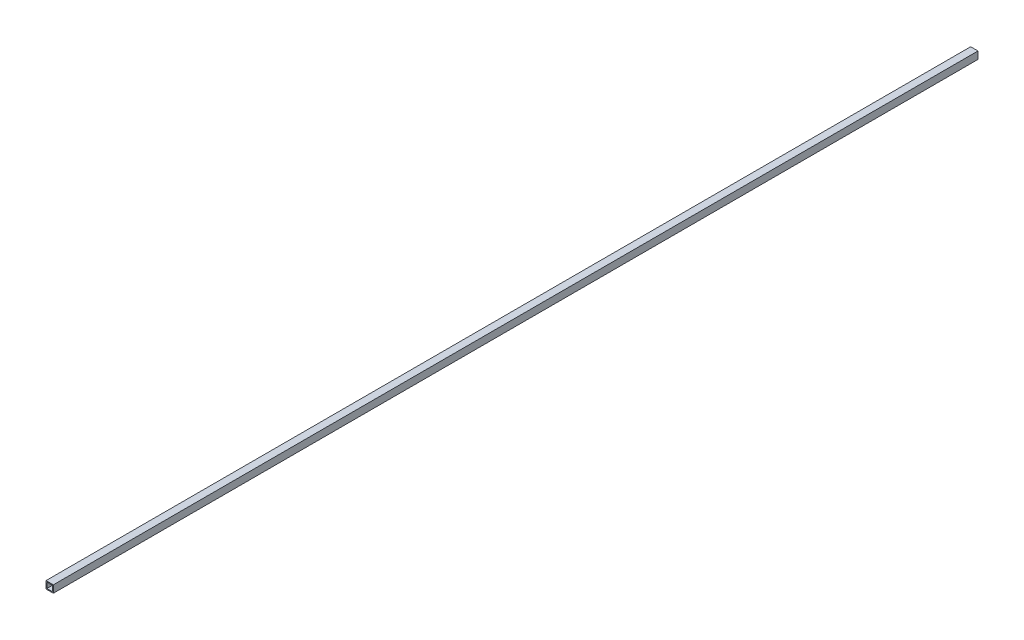
SolidWorks part; units mm, degrees
material "Thornel Mat VMA"
ref_plane "Front Plane" through (0, 0, 0) normal (0, 0, 1) x (1, 0, 0)
ref_plane "Top Plane" through (0, 0, 0) normal (0, 1, 0) x (1, 0, 0)
ref_plane "Right Plane" through (0, 0, 0) normal (1, 0, 0) x (0, 0, -1)
sketch "Sketch1" plane through (0, 0, 0) normal (0, 0, 1) x (1, 0, 0)
  line L0 (0, 0) -> (0, -4.7625) construction
  line L1 (-6.35, 6.35) -> (6.35, 6.35)
  line L2 (-6.35, 6.35) -> (-6.35, -6.35)
  line L3 (-6.35, -6.35) -> (6.35, -6.35)
  line L4 (6.35, 6.35) -> (6.35, -6.35)
  line L5 (-4.7625, 4.7625) -> (4.7625, 4.7625)
  line L6 (-4.7625, 4.7625) -> (-4.7625, -4.7625)
  line L7 (-4.7625, -4.7625) -> (4.7625, -4.7625)
  line L8 (4.7625, 4.7625) -> (4.7625, -4.7625)
  line L9 (0, 0) -> (0, 4.7625) construction
  line L10 (-4.7625, 0) -> (0, 0) construction
  line L11 (0, 0) -> (4.7625, 0) construction
  dimension "D1" = 9.525
  dimension "D2" = 9.525
  dimension "D3" = 12.7
  dimension "D4" = 6.35
extrude "Boss-Extrude1" add sketch "Sketch1" along normal blind 1600
